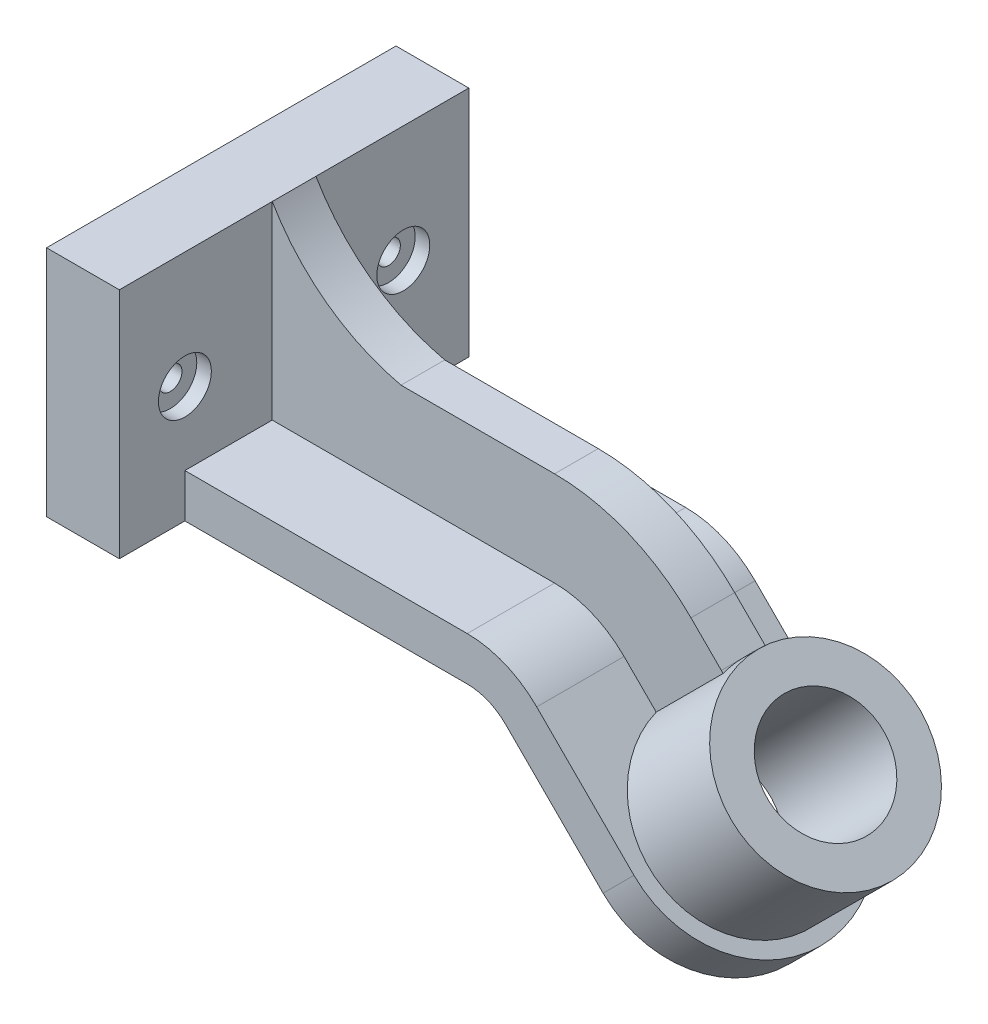
SolidWorks part; units mm, degrees
material "Mahogany"
ref_plane "Front Plane" through (0, 0, 0) normal (0, 0, 1) x (1, 0, 0)
ref_plane "Top Plane" through (0, 0, 0) normal (0, 1, 0) x (1, 0, 0)
ref_plane "Right Plane" through (0, 0, 0) normal (1, 0, 0) x (0, 0, -1)
sketch "Sketch1" plane through (0, 0, 0) normal (1, 0, 0) x (0, 0, -1)
  line L1 (-48, -32) -> (48, -32)
  line L2 (-48, -32) -> (-48, 32)
  line L3 (-48, 32) -> (48, 32)
  line L4 (48, -32) -> (48, 32)
  line L5 (-48, -32) -> (48, 32) construction
  line L6 (-48, 32) -> (48, -32) construction
  point P0 (0, 0)
  dimension "D1" = 96
  dimension "D2" = 64
extrude "Boss-Extrude1" add sketch "Sketch1" along normal blind 20
sketch "Sketch2" plane through (20, 0, 0) normal (1, 0, 0) x (0, 0, -1)
  line L0 (0, 39.8852) -> (0, -48.509) construction
  line L1 (48, 32) -> (30, 32) construction
  line L2 (48, 32) -> (-48, 32) construction
  line L3 (30, 32) -> (30, 0) construction
  dimension "D1" = 18
  dimension "D2" = 32
hole_wizard "CBORE for M6 Hex Head Bolt1" positions "3DSketch1" profile "Sketch3" counterbore size "M6" standard "BSI" end condition up to next
sketch3d "3DSketch1"
  point P0 (20, 0, -30)
sketch "Sketch3" plane through (20, 0, -30) normal (0, 1, 0) x (0, 0, -1)
  line L0 (0, 0) -> (0, 20)
  line L1 (0, 20) -> (3.2, 20)
  line L3 (3.2, 20) -> (3.2, 4)
  line L4 (3.2, 4) -> (7.2735, 4)
  line L5 (7.2735, 4) -> (7.2735, 0)
  line L7 (7.2735, 0) -> (0, 0)
  line L11 (0, -6.35) -> (0, 107.95) construction
  dimension "Thru Hole Dia." = 6.4
  dimension "Thru Hole Depth" = 20
  dimension "C'Bore Dia." = 14.547
  dimension "C'Bore Depth" = 4
ref_plane "Plane1" through (0, 0, 0) normal (0, 0, 1) x (0, -1, 0)
mirror "Mirror1" about plane through (0, 0, 0) normal (0, 0, 1) of "CBORE for M6 Hex Head Bolt1"
ref_plane "Plane2" through (0, 0, -30) normal (0, 0, 1) x (0, -1, 0)
sketch "Sketch11" plane through (0, 0, -30) normal (0, 0, 1) x (0, -1, 0)
  line L0 (32, 20) -> (32, 97.5614)
  line L1 (36.3934, 108.168) -> (84.3259, 156.1005)
  line L2 (54.6274, 143.3726) -> (32, 166)
  line L3 (-32, 20) -> (0, 20) construction
  line L4 (32, 0) -> (32, 97.5614) construction
  line L7 (-39.8852, 20) -> (48.509, 20) construction
  line L9 (20, 20) -> (32, 20)
  line L12 (20, 20) -> (20, 97.5614)
  line L13 (27.9081, 116.6533) -> (75.8406, 164.5858)
  line L14 (75.8406, 164.5858) -> (84.3259, 156.1005)
  line L15 (32, 120.7452) -> (32, 269.5194) construction
  arc A0 (32, 97.5614) -> (36.3934, 108.168) centre (47, 97.5614) cw
  arc A2 (20, 97.5614) -> (27.9081, 116.6533) centre (47, 97.5614) cw
  dimension "D6" = 15
  dimension "D7" = 12
  dimension "D3" = 64
  dimension "D4" = 146
  dimension "D5" = 45
extrude "Boss-Extrude3" add sketch "Sketch11" along normal blind 60 contours A2 L12 L9 L0 A0 L1 L14 L13
sketch "Sketch13" plane through (44.3726, 44.3726, 0) normal (0.7071, 0.7071, 0) x (0, 0, -1)
  line L1 (30, -102.2203) -> (30, -170.0071) construction
  line L2 (0, -170.0071) -> (0, -114.8712) construction
  line L3 (-30, -170.0071) -> (30, -170.0071) construction
  line L4 (-30, -140.0071) -> (-38.7349, -140.0071)
  line L5 (-38.7349, -140.0071) -> (-38.7349, -179.207)
  line L6 (-38.7349, -179.207) -> (30.8899, -179.207)
  line L7 (30.8899, -179.207) -> (30.8899, -140.0071)
  line L8 (30.8899, -140.0071) -> (30, -140.0071)
  line L9 (-30, -140.0071) -> (-38.7349, -140.0071) construction
  arc A0 (-30, -140.0071) -> (30, -140.0071) centre (0, -140.0071) ccw
  dimension "D1" = 30
extrude "Cut-Extrude1" cut sketch "Sketch13" against normal blind 12 contours A0 L4 L5 L6 L7 L8
sketch "Sketch14" plane through (44.3726, 44.3726, 0) normal (0.7071, 0.7071, 0) x (0, 0, -1)
  circle A0 centre (0, -140.0071) radius 26
  circle A1 centre (0, -140.0071) radius 16
  dimension "D1" = 52
  dimension "D2" = 32
extrude "Boss-Extrude4" add sketch "Sketch14" along normal blind 32 contours A0 | A1
ref_plane "Plane3" through (0, 0, 0) normal (0, 0, 1) x (1, 0, 0)
sketch "Sketch15" plane through (0, 0, 0) normal (0, 0, 1) x (1, 0, 0)
  line L0 (20, -20) -> (97.5614, -20) construction
  line L1 (20, -20) -> (97.5614, -20)
  line L2 (116.6533, -27.9081) -> (164.5858, -75.8406) construction
  line L3 (116.6533, -27.9081) -> (124.9878, -36.2426)
  line L4 (135.0381, -9.5233) -> (143.3726, -17.8579)
  line L5 (55.3842, 6) -> (97.5614, 6)
  line L6 (143.3726, -17.8579) -> (124.9878, -36.2426)
  line L7 (147.6152, -13.6152) -> (124.9878, -36.2426) construction
  line L8 (135.0381, -9.5233) -> (182.9706, -57.4558) construction
  line L9 (116.6533, -27.9081) -> (164.5858, -75.8406) construction
  line L10 (20, 32) -> (20, -20)
  line L13 (20, 6) -> (97.5614, 6) construction
  arc A0 (116.6533, -27.9081) -> (97.5614, -20) centre (97.5614, -47) ccw construction
  arc A1 (116.6533, -27.9081) -> (97.5614, -20) centre (97.5614, -47) ccw
  arc A2 (135.0381, -9.5233) -> (97.5614, 6) centre (97.5614, -47) ccw
  arc A3 (20, 32) -> (55.3842, 6) centre (67.5519, 59.6372) ccw
  dimension "D2" = 55
  dimension "D1" = 26
ref_plane "Plane4" through (0, 0, 6) normal (0, 0, 1) x (1, 0, 0)
sketch "Sketch16" plane through (0, 0, 6) normal (0, 0, 1) x (1, 0, 0)
  line L5 (20, 32) -> (20, -20)
  line L6 (20, -20) -> (97.5614, -20) construction
  line L7 (116.6533, -27.9081) -> (124.9878, -36.2426)
  line L8 (52.7559, -20) -> (97.5614, -20)
  line L9 (116.6533, -27.9081) -> (124.9878, -36.2426)
  line L11 (124.9878, -36.2426) -> (132.7125, -43.9673)
  line L12 (116.6533, -27.9081) -> (164.5858, -75.8406) construction
  line L13 (132.7125, -43.9673) -> (151.1596, -25.5201)
  line L14 (135.0381, -9.5233) -> (143.3726, -17.8579) construction
  line L15 (55.3842, 6) -> (97.5614, 6) construction
  line L16 (20, -20) -> (97.5614, -20)
  line L17 (135.0381, -9.5233) -> (143.3726, -17.8579)
  line L18 (55.3842, 6) -> (97.5614, 6)
  line L19 (143.3726, -17.8579) -> (151.1596, -25.5201)
  arc A5 (20, 32) -> (55.3842, 6) centre (67.5519, 59.6372) ccw construction
  arc A6 (20, 32) -> (55.3842, 6) centre (67.5519, 59.6372) ccw
  arc A7 (116.6533, -27.9081) -> (97.5614, -20) centre (97.5614, -47) ccw
  arc A8 (-2.4791, 18.9352) -> (52.7559, -20) centre (67.5519, 59.6372) ccw
  arc A9 (116.6533, -27.9081) -> (97.5614, -20) centre (97.5614, -47) ccw
  arc A10 (135.0381, -9.5233) -> (97.5614, 6) centre (97.5614, -47) ccw construction
  arc A11 (135.0381, -9.5233) -> (97.5614, 6) centre (97.5614, -47) ccw
  dimension "D1" = 26
extrude "Boss-Extrude8" add sketch "Sketch16" against normal blind 12
sketch "Sketch17" plane through (67, 67, 0) normal (0.7071, 0.7071, 0) x (0, 0, -1)
  circle A0 centre (0, -140.0071) radius 16
extrude "Cut-Extrude2" cut sketch "Sketch17" against normal through all contours A0
